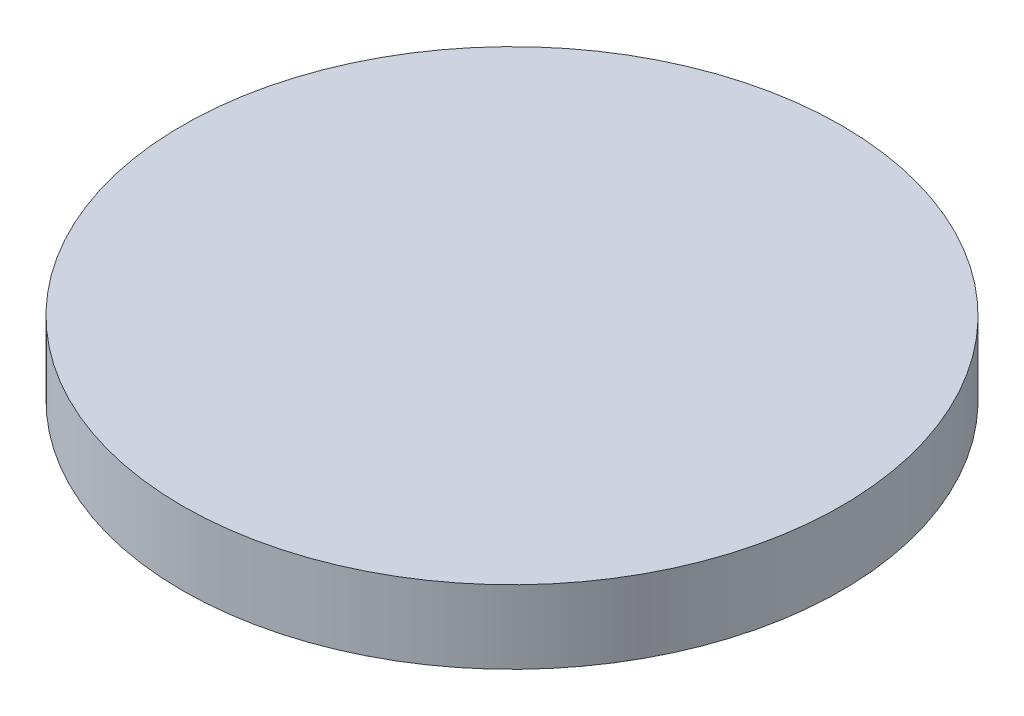
SolidWorks part; units mm, degrees
ref_plane "Front Plane" through (0, 0, 0) normal (0, 0, 1) x (1, 0, 0)
ref_plane "Top Plane" through (0, 0, 0) normal (0, 1, 0) x (1, 0, 0)
ref_plane "Right Plane" through (0, 0, 0) normal (1, 0, 0) x (0, 0, -1)
sketch "Sketch1" plane through (0, 0, 0) normal (0, 1, 0) x (1, 0, 0)
  circle A0 centre (0, 0) radius 19.05
  dimension "D1" = 38.1
extrude "Boss-Extrude1" add sketch "Sketch1" along normal blind 4.2333
sketch "Sketch2" plane through (0, 4.2333, 0) normal (0, 1, 0) x (1, 0, 0)
  circle A0 centre (0, 0) radius 9.525
  point P3 (9.525, 0)
  point P4 (0, 9.525)
  point P5 (-9.525, 0)
  point P6 (0, -9.525)
  dimension "D1" = 19.05
sketch "Sketch3" plane through (0, 0, 0) normal (0, -1, 0) x (1, 0, 0)
  circle A0 centre (0, 0) radius 9.525
  point P3 (0, 9.525)
  point P4 (9.525, 0)
  point P6 (-9.525, 0)
  point P8 (0, -9.525)
  dimension "D1" = 19.05
sketch "Sketch4" plane through (0, 0, 0) normal (0, -1, 0) x (1, 0, 0)
  circle A0 centre (0, 9.525) radius 0.635
  dimension "D1" = 1.27
extrude "Boss-Extrude2" add sketch "Sketch4" along normal blind 1.27
